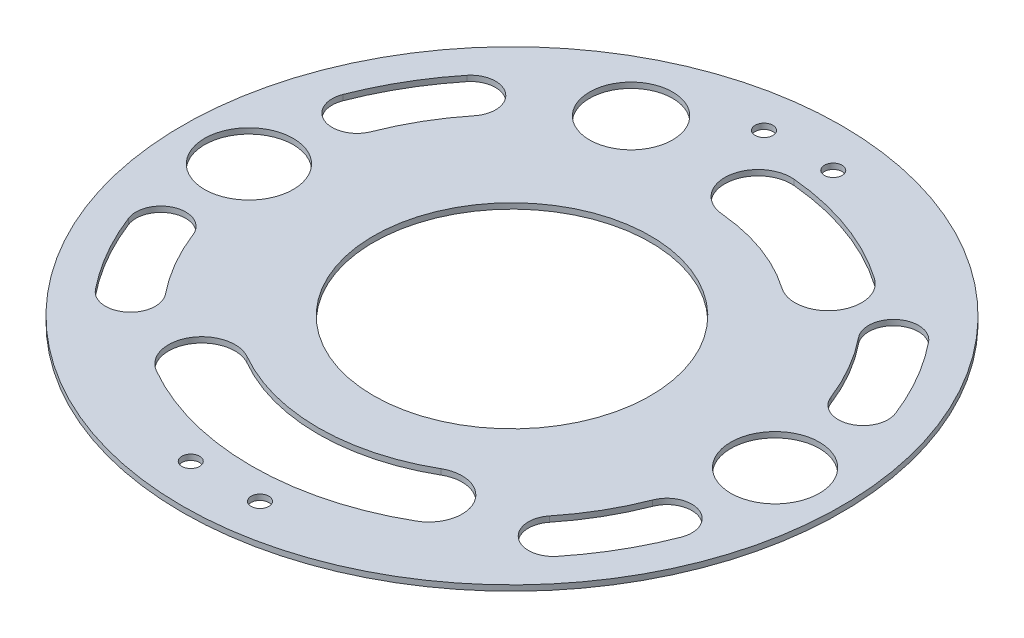
SolidWorks part; units mm, degrees
material "Thornel Mat VMA"
ref_plane "前视基准面" through (0, 0, 0) normal (0, 0, 1) x (1, 0, 0)
ref_plane "上视基准面" through (0, 0, 0) normal (0, 1, 0) x (1, 0, 0)
ref_plane "右视基准面" through (0, 0, 0) normal (1, 0, 0) x (0, 0, -1)
other "Configuration Table"
sketch "草图1" plane through (0, 0, 0) normal (0, 1, 0) x (1, 0, 0)
  line L0 (0, 0) -> (71.8737, 0) construction
  line L1 (0, 0) -> (42.4352, 24.5) construction
  line L2 (0, 0) -> (0, 51.75) construction
  line L3 (-6.25, 51.75) -> (6.25, 51.75) construction
  circle A0 centre (0, 0) radius 59.5
  circle A1 centre (0, 0) radius 25
  arc A2 (45.6852, 17.7161) -> (38.1852, 30.7065) centre (0, 0) ccw construction
  arc A3 (49.8808, 19.3431) -> (41.692, 33.5265) centre (0, 0) ccw
  arc A4 (41.4896, 16.0891) -> (34.6784, 27.8865) centre (0, 0) ccw
  arc A5 (41.4896, 16.0891) -> (49.8808, 19.3431) centre (45.6852, 17.7161) ccw
  arc A6 (41.692, 33.5265) -> (34.6784, 27.8865) centre (38.1852, 30.7065) ccw
  arc A7 (38.1852, -30.7065) -> (45.6852, -17.7161) centre (0, 0) ccw construction
  arc A8 (41.692, -33.5265) -> (49.8808, -19.3431) centre (0, 0) ccw
  arc A9 (34.6784, -27.8865) -> (41.4896, -16.0891) centre (0, 0) ccw
  arc A10 (34.6784, -27.8865) -> (41.692, -33.5265) centre (38.1852, -30.7065) ccw
  arc A11 (49.8808, -19.3431) -> (41.4896, -16.0891) centre (45.6852, -17.7161) ccw
  circle A12 centre (-6.25, 51.75) radius 1.6
  arc A17 (-45.6852, -17.7161) -> (-38.1852, -30.7065) centre (0, 0) ccw construction
  arc A18 (-49.8808, -19.3431) -> (-41.692, -33.5265) centre (0, 0) ccw
  arc A19 (-41.4896, -16.0891) -> (-34.6784, -27.8865) centre (0, 0) ccw
  arc A20 (-41.4896, -16.0891) -> (-49.8808, -19.3431) centre (-45.6852, -17.7161) ccw
  arc A21 (-41.692, -33.5265) -> (-34.6784, -27.8865) centre (-38.1852, -30.7065) ccw
  arc A22 (-38.1852, 30.7065) -> (-45.6852, 17.7161) centre (0, 0) ccw construction
  arc A23 (-41.692, 33.5265) -> (-49.8808, 19.3431) centre (0, 0) ccw
  arc A24 (-34.6784, 27.8865) -> (-41.4896, 16.0891) centre (0, 0) ccw
  arc A25 (-34.6784, 27.8865) -> (-41.692, 33.5265) centre (-38.1852, 30.7065) ccw
  arc A26 (-49.8808, 19.3431) -> (-41.4896, 16.0891) centre (-45.6852, 17.7161) ccw
  circle A41 centre (6.25, 51.75) radius 1.6
  circle A42 centre (6.25, -51.75) radius 1.6
  circle A43 centre (-6.25, -51.75) radius 1.6
  arc A44 (-7.5, -48.4226) -> (7.5, -48.4226) centre (0, 0) ccw construction
  arc A45 (-8.1888, -52.8696) -> (8.1888, -52.8696) centre (0, 0) ccw
  arc A46 (-6.8112, -43.9756) -> (6.8112, -43.9756) centre (0, 0) ccw
  arc A47 (-6.8112, -43.9756) -> (-8.1888, -52.8696) centre (-7.5, -48.4226) ccw
  arc A48 (8.1888, -52.8696) -> (6.8112, -43.9756) centre (7.5, -48.4226) ccw
  arc A49 (7.5, 48.4226) -> (-7.5, 48.4226) centre (0, 0) ccw construction
  arc A50 (8.1888, 52.8696) -> (-8.1888, 52.8696) centre (0, 0) ccw
  arc A51 (6.8112, 43.9756) -> (-6.8112, 43.9756) centre (0, 0) ccw
  arc A52 (6.8112, 43.9756) -> (8.1888, 52.8696) centre (7.5, 48.4226) ccw
  arc A53 (-8.1888, 52.8696) -> (-6.8112, 43.9756) centre (-7.5, 48.4226) ccw
  point P6 (42.4352, 24.5)
  point P18 (42.4352, -24.5)
  point P29 (0, 51.75)
  point P32 (-42.4352, -24.5)
  point P39 (-42.4352, 24.5)
  point P47 (0, -49)
  point P51 (0, 0)
  point P53 (0, 49)
  point P66 (0, -49)
  point P74 (0, 49)
  dimension "D1" = 119
  dimension "D2" = 50
  dimension "D5" = 15
  dimension "D6" = 4.5
  dimension "D10" = 3.2
  dimension "D3" = 30
  dimension "D4" = 49
  dimension "D8" = 12.5
  dimension "D9" = 51.75
  dimension "D7" = 6
extrude "凸台-拉伸1" add sketch "草图1" along normal blind 1
sketch "草图2" plane through (0, 0, 0) normal (0, -1, 0) x (1, 0, 0)
  line L0 (0, 0) -> (0, 41) construction
  line L1 (14.0228, -38.5274) -> (0, 0) construction
  line L2 (23.5166, -33.5852) -> (0, 0) construction
  arc A0 (3.5734, -40.844) -> (23.5166, -33.5852) centre (0, 0) ccw construction
  arc A1 (4.0963, -46.8212) -> (26.9581, -38.5001) centre (0, 0) ccw
  arc A2 (3.0505, -34.8668) -> (20.0752, -28.6703) centre (0, 0) ccw
  arc A3 (3.0505, -34.8668) -> (4.0963, -46.8212) centre (3.5734, -40.844) ccw
  arc A4 (26.9581, -38.5001) -> (20.0752, -28.6703) centre (23.5166, -33.5852) ccw
  arc A5 (-20.5, 35.507) -> (20.5, 35.507) centre (0, 0) cw construction
  arc A7 (23.5, 40.7032) -> (-23.5, 40.7032) centre (0, 0) ccw
  arc A8 (17.5, 30.3109) -> (-17.5, 30.3109) centre (0, 0) ccw
  arc A9 (17.5, 30.3109) -> (23.5, 40.7032) centre (20.5, 35.507) ccw
  arc A10 (-23.5, 40.7032) -> (-17.5, 30.3109) centre (-20.5, 35.507) ccw
  circle A11 centre (47.5, 0) radius 8
  circle A12 centre (-47.5, 0) radius 8
  circle A13 centre (-20.5, -42) radius 7.5
  point P5 (14.0228, -38.5274)
  point P17 (0, 41)
  dimension "D1" = 16
  dimension "D2" = 15
  dimension "D3" = 6
  dimension "D4" = 160
extrude "切除-拉伸1" cut sketch "草图2" against normal blind 10
